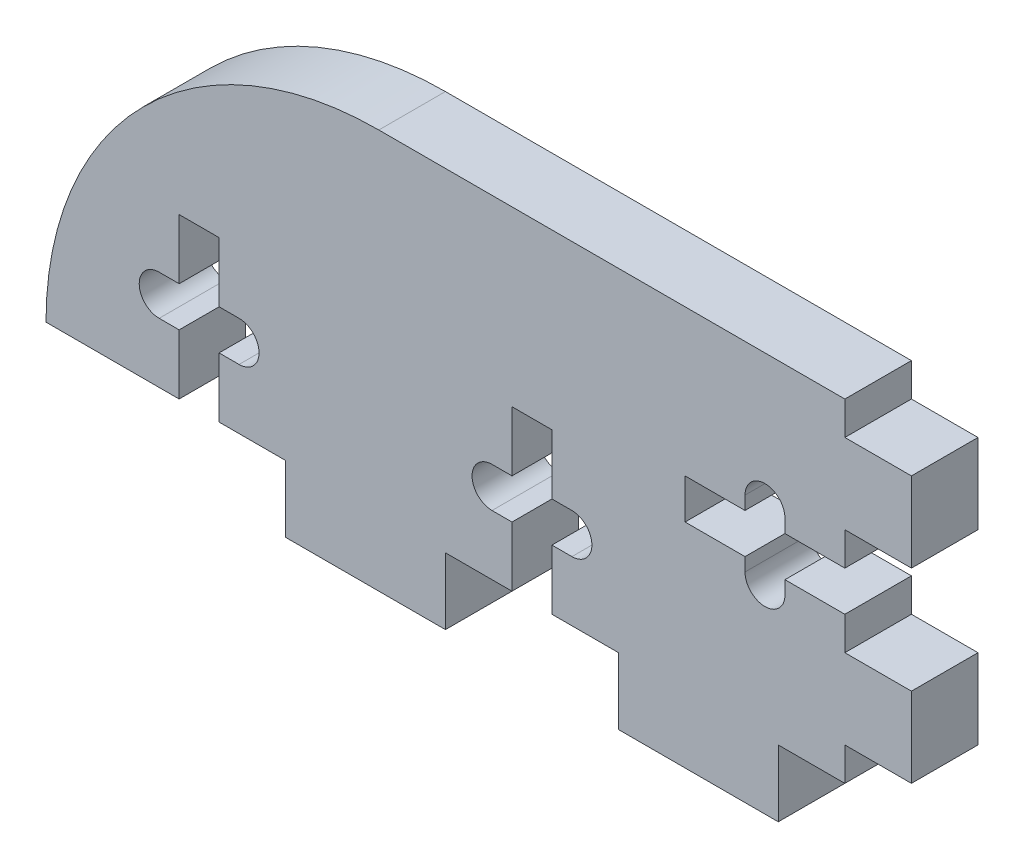
SolidWorks part; units mm, degrees
ref_plane "Front Plane" through (0, 0, 0) normal (0, 0, 1) x (1, 0, 0)
ref_plane "Top Plane" through (0, 0, 0) normal (0, 1, 0) x (1, 0, 0)
ref_plane "Right Plane" through (0, 0, 0) normal (1, 0, 0) x (0, 0, -1)
sketch "Sketch1" plane through (0, 0, 0) normal (0, 0, 1) x (1, 0, 0)
  line L1 (23.964, -5.8409) -> (18.964, -5.8409)
  line L2 (23.964, -5.8409) -> (23.964, -3.3409)
  line L3 (23.964, 19.1591) -> (-11.036, 19.1591)
  line L4 (23.964, 16.6591) -> (28.964, 16.6591)
  line L5 (23.964, 2.6591) -> (23.964, 5.1591)
  line L6 (23.964, 10.6591) -> (28.964, 10.6591)
  line L7 (28.964, 16.6591) -> (28.964, 10.6591)
  line L8 (23.964, 16.6591) -> (23.964, 19.1591)
  line L9 (23.964, 2.6591) -> (28.964, 2.6591)
  line L10 (11.964, 5.1591) -> (16.464, 5.1591)
  line L11 (23.964, -3.3409) -> (28.964, -3.3409)
  line L12 (28.964, 2.6591) -> (28.964, -3.3409)
  line L13 (11.964, 5.1591) -> (11.964, 8.1591)
  line L14 (17.964, 9.1591) -> (17.964, 4.1591) construction
  line L15 (11.964, 8.1591) -> (16.464, 8.1591)
  line L16 (11.964, 5.1591) -> (23.964, 8.1591) construction
  line L17 (23.964, 5.1591) -> (11.964, 8.1591) construction
  line L18 (23.964, 8.1591) -> (23.964, 10.6591)
  line L19 (19.464, 9.1591) -> (19.464, 8.1591)
  line L20 (16.464, 9.1591) -> (16.464, 8.1591)
  line L21 (-21.536, -1.3409) -> (-23.036, -1.3409)
  line L22 (19.464, 8.1591) -> (23.964, 8.1591)
  line L23 (-23.036, -1.3409) -> (-23.036, -5.8409)
  line L24 (19.464, 5.1591) -> (19.464, 4.1591)
  line L25 (19.464, 5.1591) -> (23.964, 5.1591)
  line L26 (16.464, 5.1591) -> (16.464, 4.1591)
  line L27 (-26.036, -1.3409) -> (-27.536, -1.3409)
  line L28 (-26.036, -1.3409) -> (-26.036, -5.8409)
  line L29 (-26.036, -5.8409) -> (-23.036, 6.1591) construction
  line L30 (-23.036, 6.1591) -> (-23.036, 1.6591)
  line L31 (-21.536, 0.1591) -> (-27.536, 0.1591) construction
  line L32 (-26.036, 1.6591) -> (-27.536, 1.6591)
  line L33 (-26.036, 6.1591) -> (-23.036, -5.8409) construction
  line L34 (-21.536, 1.6591) -> (-23.036, 1.6591)
  line L35 (-26.036, 6.1591) -> (-26.036, 1.6591)
  line L36 (-26.036, 6.1591) -> (-23.036, 6.1591)
  line L37 (3.464, -1.3409) -> (1.964, -1.3409)
  line L38 (1.964, -1.3409) -> (1.964, -5.8409)
  line L39 (-1.036, -1.3409) -> (-2.536, -1.3409)
  line L40 (-1.036, -1.3409) -> (-1.036, -5.8409)
  line L41 (1.964, 6.1591) -> (1.964, 1.6591)
  line L42 (-1.036, 1.6591) -> (-2.536, 1.6591)
  line L43 (3.464, 1.6591) -> (1.964, 1.6591)
  line L44 (-1.036, 6.1591) -> (-1.036, 1.6591)
  line L45 (-1.036, 6.1591) -> (1.964, 6.1591)
  line L46 (-1.036, -5.8409) -> (1.964, 6.1591) construction
  line L47 (3.464, 0.1591) -> (-2.536, 0.1591) construction
  line L48 (-1.036, 6.1591) -> (1.964, -5.8409) construction
  line L49 (-26.036, -5.8409) -> (-36.036, -5.8409)
  line L50 (-1.036, -5.8409) -> (-6.036, -5.8409)
  line L51 (-18.036, -5.8409) -> (-23.036, -5.8409)
  line L53 (6.964, -5.8409) -> (6.964, -10.8409)
  line L54 (6.964, -10.8409) -> (18.964, -10.8409)
  line L55 (18.964, -5.8409) -> (18.964, -10.8409)
  line L56 (6.964, -5.8409) -> (1.964, -5.8409)
  line L57 (-18.036, -5.8409) -> (-18.036, -10.8409)
  line L58 (-18.036, -10.8409) -> (-6.036, -10.8409)
  line L59 (-6.036, -5.8409) -> (-6.036, -10.8409)
  arc A0 (-11.036, 19.1591) -> (-36.036, -5.8409) centre (-11.036, -5.8409) ccw
  arc A1 (19.464, 9.1591) -> (16.464, 9.1591) centre (17.964, 9.1591) ccw
  arc A2 (16.464, 4.1591) -> (19.464, 4.1591) centre (17.964, 4.1591) ccw
  arc A3 (-21.536, -1.3409) -> (-21.536, 1.6591) centre (-21.536, 0.1591) ccw
  arc A4 (-27.536, 1.6591) -> (-27.536, -1.3409) centre (-27.536, 0.1591) ccw
  arc A5 (-2.536, 1.6591) -> (-2.536, -1.3409) centre (-2.536, 0.1591) ccw
  arc A6 (3.464, -1.3409) -> (3.464, 1.6591) centre (3.464, 0.1591) ccw
  point P17 (17.964, 6.6591)
  point P19 (17.964, 6.6591)
  point P30 (-24.536, 0.1591)
  point P34 (-24.536, 0.1591)
  point P51 (0.464, 0.1591)
  point P53 (0.464, 0.1591)
  dimension "D3" = 3
  dimension "D1" = 25
  dimension "D2" = 60
  dimension "D4" = 12
  dimension "D5" = 2.5
  dimension "D6" = 2.5
  dimension "D7" = 2.5
  dimension "D8" = 2.5
  dimension "D9" = 3
  dimension "D10" = 8
  dimension "D11" = 12
  dimension "D12" = 3
  dimension "D13" = 10
  dimension "D14" = 6
  dimension "D15" = 3
  dimension "D16" = 2
  dimension "D17" = 5
  dimension "D18" = 5
  dimension "D19" = 5
  dimension "D20" = 5
  dimension "D21" = 5
extrude "Boss-Extrude1" add sketch "Sketch1" along normal blind 5
